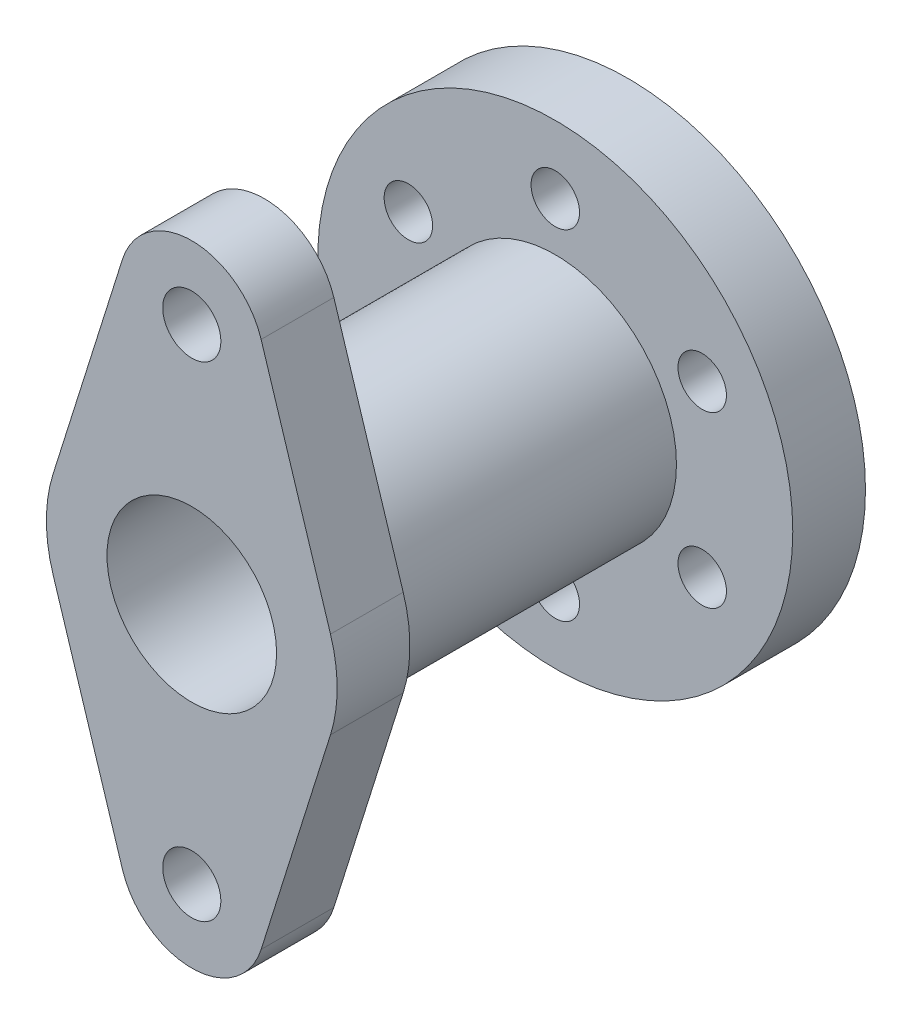
SolidWorks part; units mm, degrees
material "Brass"
ref_plane "Front Plane" through (0, 0, 0) normal (0, 0, 1) x (1, 0, 0)
ref_plane "Top Plane" through (0, 0, 0) normal (0, 1, 0) x (1, 0, 0)
ref_plane "Right Plane" through (0, 0, 0) normal (1, 0, 0) x (0, 0, -1)
sketch "Sketch1" plane through (0, 0, 0) normal (0, 0, 1) x (1, 0, 0)
  circle A0 centre (0, 0) radius 1244.6
  dimension "D1" = 2489.2
extrude "Boss-Extrude1" add sketch "Sketch1" along normal mid plane 381
sketch "Sketch2" plane through (0, 0, 190.5) normal (0, 0, 1) x (1, 0, 0)
  circle A0 centre (0, 0) radius 889 construction
  circle A1 centre (0, 889) radius 127
  circle A2 centre (769.8966, 444.5) radius 127
  circle A3 centre (769.8966, -444.5) radius 127
  circle A4 centre (0, -889) radius 127
  circle A5 centre (-769.8966, -444.5) radius 127
  circle A6 centre (-769.8966, 444.5) radius 127
  circle A7 centre (0, 0) radius 1244.6 construction
  point P17 (0, 0)
  dimension "D1" = 1778
  dimension "D2" = 254
  dimension "D3" = 6
extrude "Cut-Extrude1" cut sketch "Sketch2" against normal through all
sketch "Sketch3" plane through (0, 0, 190.5) normal (0, 0, 1) x (1, 0, 0)
  circle A0 centre (0, 0) radius 635
  dimension "D1" = 1270
extrude "Boss-Extrude2" add sketch "Sketch3" along normal blind 1524
sketch "Sketch5" plane through (0, 0, 1714.5) normal (0, 0, 1) x (1, 0, 0)
  line L0 (0, 2540) -> (0, -2540) construction
  line L1 (-798.793, 0) -> (798.793, 0) construction
  line L2 (-363.4508, 1384.3) -> (-726.9017, 228.6)
  line L3 (-726.9017, -228.6) -> (-363.4508, -1384.3)
  line L4 (363.4508, -1384.3) -> (726.9017, -228.6)
  line L5 (726.9017, 228.6) -> (363.4508, 1384.3)
  arc A0 (363.4508, -1384.3) -> (-363.4508, -1384.3) centre (0, -1270) cw
  arc A1 (363.4508, 1384.3) -> (-363.4508, 1384.3) centre (0, 1270) ccw
  arc A2 (-726.9017, -228.6) -> (-726.9017, 228.6) centre (0, 0) cw
  arc A3 (726.9017, 228.6) -> (726.9017, -228.6) centre (0, 0) cw
  circle A4 centre (0, 1270) radius 152.4
  circle A5 centre (0, -1270) radius 152.4
  dimension "D1" = 381
  dimension "D3" = 762
  dimension "D4" = 762
  dimension "D5" = 304.8
  dimension "D2" = 2540
extrude "Boss-Extrude3" add sketch "Sketch5" along normal blind 381
sketch "Sketch6" plane through (0, 0, 2095.5) normal (0, 0, 1) x (1, 0, 0)
  circle A0 centre (0, 0) radius 444.5
  point P2 (0, 0)
  dimension "D1" = 889
extrude "Boss-Extrude4" add sketch "Sketch6" against normal blind 762
sketch "Sketch7" plane through (0, 0, 2095.5) normal (0, 0, 1) x (1, 0, 0)
  circle A0 centre (0, 0) radius 444.5
  dimension "D1" = 889
extrude "Cut-Extrude2" cut sketch "Sketch7" against normal blind 762
sketch "Sketch8" plane through (0, 0, 1333.5) normal (0, 0, 1) x (1, 0, 0)
  circle A0 centre (0, 0) radius 330.2
  dimension "D1" = 660.4
extrude "Cut-Extrude3" cut sketch "Sketch8" against normal through all
